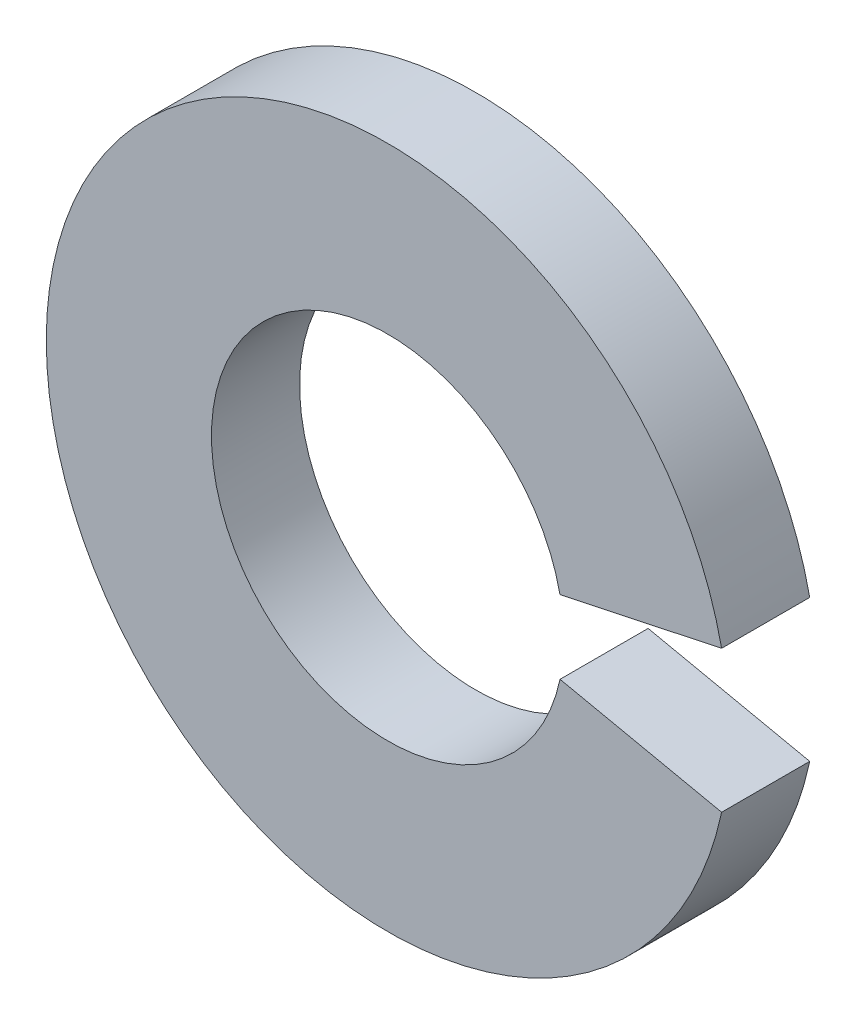
SolidWorks part; units mm, degrees
ref_plane "前视基准面" through (0, 0, 0) normal (0, 0, 1) x (1, 0, 0)
ref_plane "上视基准面" through (0, 0, 0) normal (0, 1, 0) x (1, 0, 0)
ref_plane "右视基准面" through (0, 0, 0) normal (1, 0, 0) x (0, 0, -1)
other "Configuration Table"
sketch "草图1" plane through (0, 0, 0) normal (0, 0, 1) x (1, 0, 0)
  line L0 (3.0323, -0.6445) -> (1.565, -0.3327)
  line L1 (1.565, 0.3327) -> (3.0323, 0.6445)
  arc A0 (3.0323, 0.6445) -> (3.0323, -0.6445) centre (0, 0) ccw
  arc A1 (1.565, -0.3327) -> (1.565, 0.3327) centre (0, 0) cw
extrude "凸台-拉伸1" add sketch "草图1" along normal mid plane 0.8
